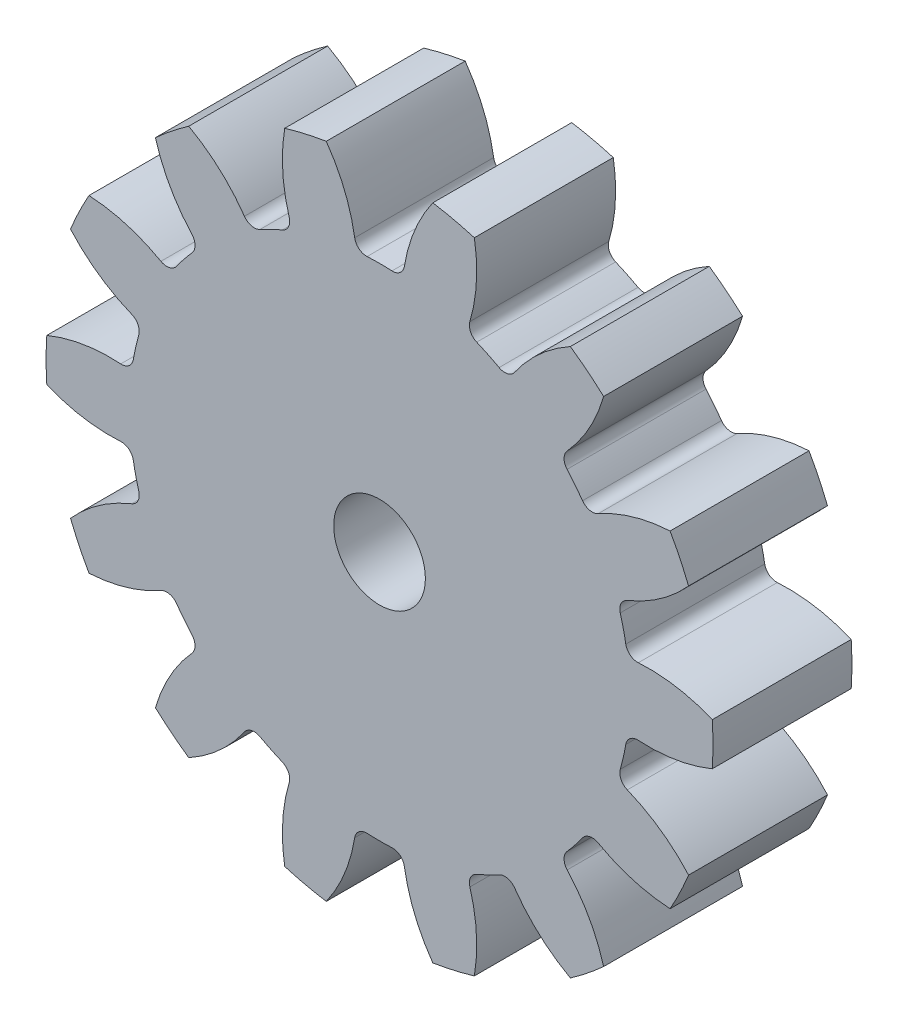
SolidWorks part; units mm, degrees
ref_plane "Front" through (0, 0, 0) normal (0, 0, 1) x (1, 0, 0)
ref_plane "Top" through (0, 0, 0) normal (0, 1, 0) x (1, 0, 0)
ref_plane "Right" through (0, 0, 0) normal (1, 0, 0) x (0, 0, -1)
sketch "Sketch1" plane through (0, 0, 0) normal (0, 0, 1) x (1, 0, 0)
  circle A0 centre (0, 0) radius 9
  circle A1 centre (0, 0) radius 12
  circle A2 centre (0, 0) radius 10.5
  dimension "D1" = 24
  dimension "D2" = 18
  dimension "D3" = 21
extrude "Boss-Extrude1" add sketch "Sketch1" along normal mid plane 5 contours A1
sketch "Sketch3" plane through (0, 0, 0) normal (0, 0, 1) x (1, 0, 0)
  line L0 (0, 0) -> (0, 12) construction
  line L1 (0, 0) -> (-0.8438, 8.9604) construction
  line L2 (-1.1756, 10.434) -> (1.1756, 10.434) construction
  line L3 (-1.7015, 11.8788) -> (0, 7.204) construction
  line L4 (1.1756, 10.434) -> (3.4679, 9.9108) construction
  line L5 (2.6703, 11.6991) -> (0, 0) construction
  arc A0 (-0.8438, 8.9604) -> (0.8438, 8.9604) centre (0, 0) cw
  arc A4 (1.9175, 11.8458) -> (-1.9175, 11.8458) centre (0, 0) ccw
  circle A5 centre (0, 0) radius 12 construction
  arc A7 (-1.9175, 11.8458) -> (-0.8438, 8.9604) centre (-6.7534, 8.4038) cw
  arc A10 (1.9175, 11.8458) -> (0.8438, 8.9604) centre (6.7534, 8.4038) ccw
  circle A11 centre (0, 0) radius 9 construction
  circle A12 centre (0, 0) radius 10.5 construction
  dimension "D1" = 20
  dimension "D2" = 12.857
extrude "Cut-Extrude1" cut sketch "Sketch3" against normal through all both and the other way through all contours A10 A4 A7 A0
fillet "Fillet2" radius 0.43 2 edges at (-0.8438, 8.9604, 0) (0.8438, 8.9604, 0)
pattern_circular "CirPattern1" count 14 over 360 about axis through (0, 0, 0) along (0, 0, 1) of "Cut-Extrude1", "Fillet2"
sketch "Sketch4" plane through (0, 0, 0) normal (0, 0, 1) x (1, 0, 0)
  circle A0 centre (0, 0) radius 1.65
  dimension "D1" = 3.3
extrude "Through_Center_Hole" cut sketch "Sketch4" against normal through all both and the other way through all
equation "\"od\" = 24'outside diameter"
equation "\"n\"= 14'number of teeth"
equation "\"m\"= \"od\" / ( \"n\" + 2 )'module"
equation "\"p\"= \"m\" * pi'pitch"
equation "\"d\"= \"m\" * \"n\"'primitive diameter"
equation "\"da\"= \"d\" + 2 * \"m\"'head diamater"
equation "\"df\"= \"d\" - 2 * \"m\"'foot diameter"
equation "\"D1@Sketch1\"=\"od\""
equation "\"D2@Sketch1\"=\"df\""
equation "\"D3@Sketch1\"=\"d\""
equation "\"D2@Sketch3\"=180/\"n\""
equation "\"D1@CirPattern1\"=\"n\""
